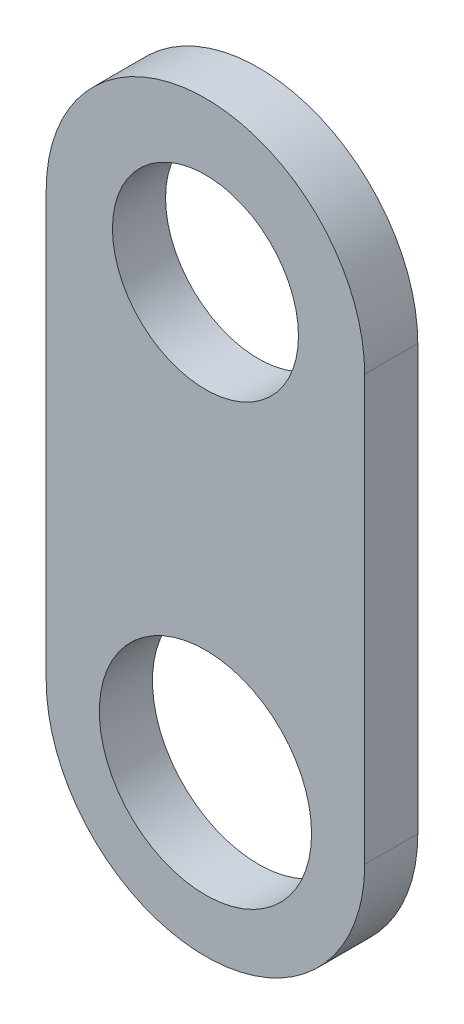
SolidWorks part; units mm, degrees
material "6061-T6 (SS)"
ref_plane "Front Plane" through (0, 0, 0) normal (0, 0, 1) x (1, 0, 0)
ref_plane "Top Plane" through (0, 0, 0) normal (0, 1, 0) x (1, 0, 0)
ref_plane "Right Plane" through (0, 0, 0) normal (1, 0, 0) x (0, 0, -1)
sketch "Sketch2" plane through (0, 0, 0) normal (0, 0, 1) x (1, 0, 0)
  line L0 (0, 0) -> (0, 50.8) construction
  line L1 (-19.05, 0) -> (-19.05, 50.8)
  line L2 (19.05, 0) -> (19.05, 50.8)
  arc A0 (-19.05, 0) -> (19.05, 0) centre (0, 0) ccw
  arc A1 (19.05, 50.8) -> (-19.05, 50.8) centre (0, 50.8) ccw
  circle A2 centre (0, 50.8) radius 11.1252
  circle A3 centre (0, 0) radius 12.6937
  point P3 (0, 25.4)
  dimension "D3" = 22.2504
  dimension "D4" = 25.3873
  dimension "D1" = 38.1
  dimension "D2" = 50.8
extrude "Boss-Extrude1" add sketch "Sketch2" along normal mid plane 6.35
equation "\"Link Width\"= 1.5in"
equation "\"Hole Spacing\"= 2in"
equation "\"Link Thickness\"= 0.25in"
equation "\"Bracket Bar Diameter\" = \"Bar Diameter\""
equation "\"Second Shaft Diameter\"= 1in"
equation "\"D1@Sketch2\"=\"Link Width\""
equation "\"D2@Sketch2\"=\"Hole Spacing\""
equation "\"D1@Boss-Extrude1\"=\"Link Thickness\""
equation "\"D3@Sketch2\" = \"Bracket Hole Diameter\""
equation "\"D4@Sketch2\" = \"Shaft Hole Diameter\""
equation "\"Bar Diameter\"= 0.875in"
equation "\"Bracket Hole Diameter\" = \"Bracket Bar Diameter\" + 0.001in"
equation "\"Shaft Hole Diameter\" = \"Second Shaft Diameter\" - 0.0005in"
